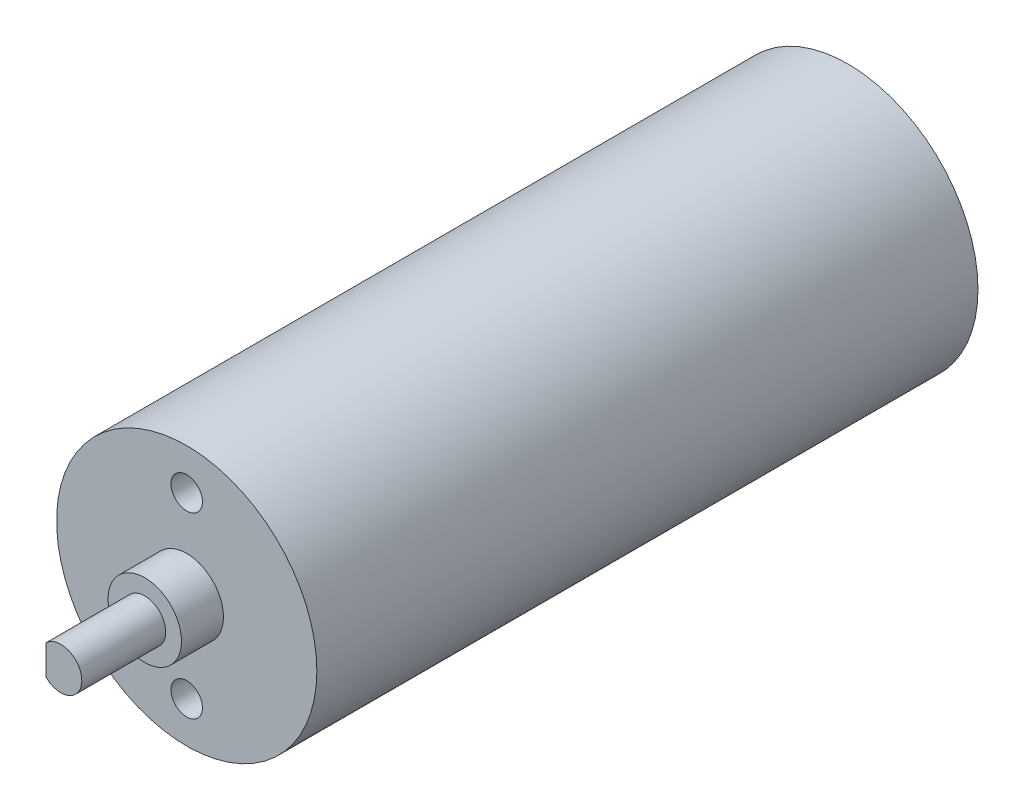
SolidWorks part; units mm, degrees
material "1100-H12 棒材(SS)"
ref_plane "前视基准面" through (0, 0, 0) normal (0, 0, 1) x (1, 0, 0)
ref_plane "上视基准面" through (0, 0, 0) normal (0, 1, 0) x (1, 0, 0)
ref_plane "右视基准面" through (0, 0, 0) normal (1, 0, 0) x (0, 0, -1)
sketch "草图1" plane through (0, 0, 0) normal (0, 0, 1) x (1, 0, 0)
  circle A0 centre (0, 0) radius 12.4
  dimension "D1" = 24.8
extrude "凸台-拉伸1" add sketch "草图1" along normal blind 63
sketch "草图2" plane through (0, 0, 63) normal (0, 0, 1) x (1, 0, 0)
  circle A0 centre (0, 0) radius 3.5
  dimension "D1" = 7
extrude "凸台-拉伸2" add sketch "草图2" along normal blind 4
sketch "草图3" plane through (0, 0, 67) normal (0, 0, 1) x (1, 0, 0)
  line L0 (-1.41, 1.4184) -> (-1.41, -1.4184)
  arc A0 (-1.41, -1.4184) -> (-1.41, 1.4184) centre (0, 0) ccw
  dimension "D1" = 4
  dimension "D2" = 1.41
extrude "凸台-拉伸3" add sketch "草图3" along normal blind 8
sketch "草图4" plane through (0, 0, 63) normal (0, 0, 1) x (1, 0, 0)
  circle A0 centre (0, 0) radius 8.5 construction
  circle A1 centre (0, -8.5) radius 1.5
  circle A2 centre (0, 8.5) radius 1.5
  dimension "D1" = 17
  dimension "D2" = 3
extrude "切除-拉伸1" cut sketch "草图4" against normal blind 10
